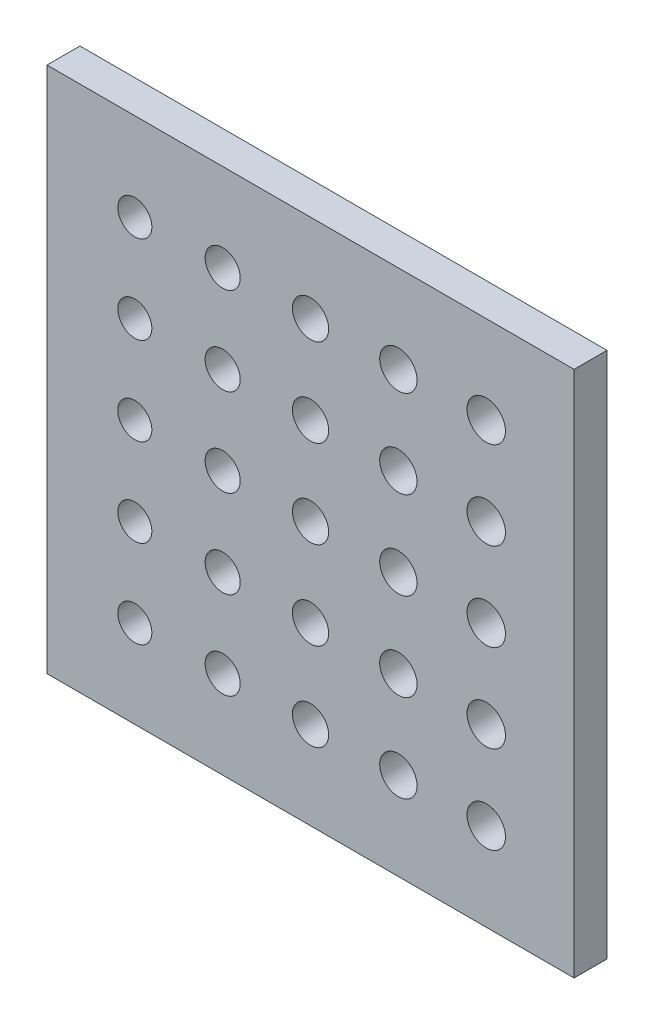
SolidWorks part; units mm, degrees
ref_plane "Front Plane" through (0, 0, 0) normal (0, 0, 1) x (1, 0, 0)
ref_plane "Top Plane" through (0, 0, 0) normal (0, 1, 0) x (1, 0, 0)
ref_plane "Right Plane" through (0, 0, 0) normal (1, 0, 0) x (0, 0, -1)
sketch "草图1" plane through (0, 0, 0) normal (0, 0, 1) x (1, 0, 0)
  line L1 (48, 48) -> (0, 48)
  line L2 (48, 48) -> (48, 0)
  line L3 (48, 0) -> (0, 0)
  line L4 (0, 48) -> (0, 0)
  circle A0 centre (8, 8) radius 1.55
  circle A1 centre (8, 16) radius 1.55
  circle A2 centre (8, 24) radius 1.55
  circle A3 centre (8, 32) radius 1.55
  circle A4 centre (8, 40) radius 1.55
  circle A5 centre (16, 8) radius 1.6
  circle A6 centre (16, 16) radius 1.6
  circle A7 centre (16, 24) radius 1.6
  circle A8 centre (16, 32) radius 1.6
  circle A9 centre (16, 40) radius 1.6
  circle A10 centre (24, 8) radius 1.65
  circle A11 centre (24, 16) radius 1.65
  circle A12 centre (24, 24) radius 1.65
  circle A13 centre (24, 32) radius 1.65
  circle A14 centre (24, 40) radius 1.65
  circle A15 centre (32, 8) radius 1.7
  circle A16 centre (32, 16) radius 1.7
  circle A17 centre (32, 24) radius 1.7
  circle A18 centre (32, 32) radius 1.7
  circle A19 centre (32, 40) radius 1.7
  circle A20 centre (40, 8) radius 1.75
  circle A21 centre (40, 16) radius 1.75
  circle A22 centre (40, 24) radius 1.75
  circle A23 centre (40, 32) radius 1.75
  circle A24 centre (40, 40) radius 1.75
  dimension "D1" = 5
  dimension "D2" = 5
  dimension "D3" = 5
  dimension "D4" = 5
  dimension "D5" = 5
extrude "凸台-拉伸1" add sketch "草图1" along normal blind 3
